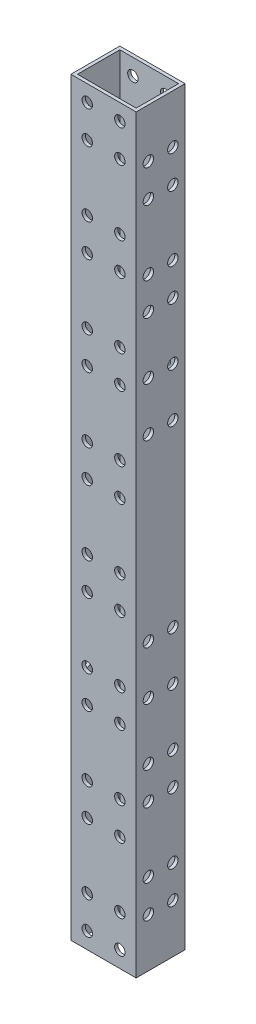
SolidWorks part; units mm, degrees
ref_plane "前视基准面" through (0, 0, 0) normal (0, 0, 1) x (1, 0, 0)
ref_plane "上视基准面" through (0, 0, 0) normal (0, 1, 0) x (1, 0, 0)
ref_plane "右视基准面" through (0, 0, 0) normal (1, 0, 0) x (0, 0, -1)
other "Configuration Table"
sketch "草图1" plane through (0, 0, 0) normal (0, 1, 0) x (1, 0, 0)
  line L1 (-10, -7.5) -> (10, -7.5)
  line L2 (-10, -7.5) -> (-10, 7.5)
  line L3 (-10, 7.5) -> (10, 7.5)
  line L4 (10, -7.5) -> (10, 7.5)
  line L5 (-10, -7.5) -> (10, 7.5) construction
  line L6 (-10, 7.5) -> (10, -7.5) construction
  point P0 (0, 0)
  dimension "D1" = 20
  dimension "D2" = 15
extrude "拉伸-薄壁1" add sketch "草图1" along normal blind 230 thin thin type one direction reverse wall 1
sketch "草图3" plane through (10, 0, 0) normal (1, 0, 0) x (0, 0, -1)
  line L0 (-7.5, 115) -> (7.5, 115) construction
  line L1 (-7.5, 230) -> (-7.5, 0) construction
  line L2 (7.5, 230) -> (7.5, 0) construction
  line L3 (0, 375) -> (0, 394.0699) construction
  line L4 (-7.5, 150) -> (7.5, 150) construction
  line L5 (-7.5, 210) -> (7.5, 210) construction
  line L6 (-7.5, 230) -> (7.5, 230) construction
  line L7 (-7.5, 20) -> (7.5, 20) construction
  circle A0 centre (-3.75, 157.5) radius 1.6
  circle A1 centre (-3.75, 142.5) radius 1.6
  circle A2 centre (3.75, 142.5) radius 1.6
  circle A3 centre (3.75, 157.5) radius 1.6
  circle A4 centre (-3.75, 87.5) radius 1.6
  circle A5 centre (3.75, 87.5) radius 1.6
  circle A6 centre (3.75, 72.5) radius 1.6
  circle A7 centre (-3.75, 72.5) radius 1.6
  circle A8 centre (-3.75, 215) radius 1.6
  circle A9 centre (3.75, 215) radius 1.6
  circle A10 centre (3.75, 205) radius 1.6
  circle A11 centre (-3.75, 205) radius 1.6
  circle A12 centre (-3.75, 185) radius 1.6
  circle A13 centre (3.75, 185) radius 1.6
  circle A14 centre (-3.75, 175) radius 1.6
  circle A15 centre (3.75, 175) radius 1.6
  circle A16 centre (3.75, 55) radius 1.6
  circle A17 centre (-3.75, 55) radius 1.6
  circle A18 centre (3.75, 45) radius 1.6
  circle A19 centre (-3.75, 45) radius 1.6
  circle A20 centre (-3.75, 25) radius 1.6
  circle A21 centre (3.75, 25) radius 1.6
  circle A22 centre (3.75, 15) radius 1.6
  circle A23 centre (-3.75, 15) radius 1.6
  dimension "D4" = 3.2
  dimension "D6" = 3.2
  dimension "D1" = 35
  dimension "D2" = 3.75
  dimension "D3" = 7.5
  dimension "D5" = 20
  dimension "D7" = 3.75
  dimension "D8" = 5
  dimension "D9" = 30
extrude "切除-拉伸1" cut sketch "草图3" against normal through all
sketch "草图4" plane through (0, 0, -7.5) normal (0, 0, -1) x (-1, 0, 0)
  line L0 (-10, 220) -> (10, 220) construction
  line L1 (-10, 230) -> (-10, 0) construction
  line L2 (10, 230) -> (10, 0) construction
  line L3 (0, 230) -> (0, 220) construction
  line L4 (-10, 230) -> (10, 230) construction
  circle A0 centre (5, 225) radius 1.6
  circle A1 centre (-5, 225) radius 1.6
  circle A2 centre (5, 215) radius 1.6
  circle A3 centre (-5, 215) radius 1.6
  circle A4 centre (-5, 195) radius 1.6
  circle A5 centre (5, 195) radius 1.6
  circle A6 centre (-5, 185) radius 1.6
  circle A7 centre (5, 185) radius 1.6
  circle A8 centre (-5, 165) radius 1.6
  circle A9 centre (5, 165) radius 1.6
  circle A10 centre (-5, 155) radius 1.6
  circle A11 centre (5, 155) radius 1.6
  circle A12 centre (-5, 135) radius 1.6
  circle A13 centre (5, 135) radius 1.6
  circle A14 centre (-5, 125) radius 1.6
  circle A15 centre (5, 125) radius 1.6
  circle A16 centre (-5, 105) radius 1.6
  circle A17 centre (5, 105) radius 1.6
  circle A18 centre (-5, 95) radius 1.6
  circle A19 centre (5, 95) radius 1.6
  circle A20 centre (-5, 75) radius 1.6
  circle A21 centre (5, 75) radius 1.6
  circle A22 centre (-5, 65) radius 1.6
  circle A23 centre (5, 65) radius 1.6
  circle A24 centre (-5, 45) radius 1.6
  circle A25 centre (5, 45) radius 1.6
  circle A26 centre (-5, 35) radius 1.6
  circle A27 centre (5, 35) radius 1.6
  circle A28 centre (-5, 15) radius 1.6
  circle A29 centre (5, 15) radius 1.6
  circle A30 centre (-5, 5) radius 1.6
  circle A31 centre (5, 5) radius 1.6
  dimension "D2" = 3.2
  dimension "D1" = 10
  dimension "D3" = 5
  dimension "D4" = 5
  dimension "D5" = 30
extrude "切除-拉伸2" cut sketch "草图4" against normal through all
